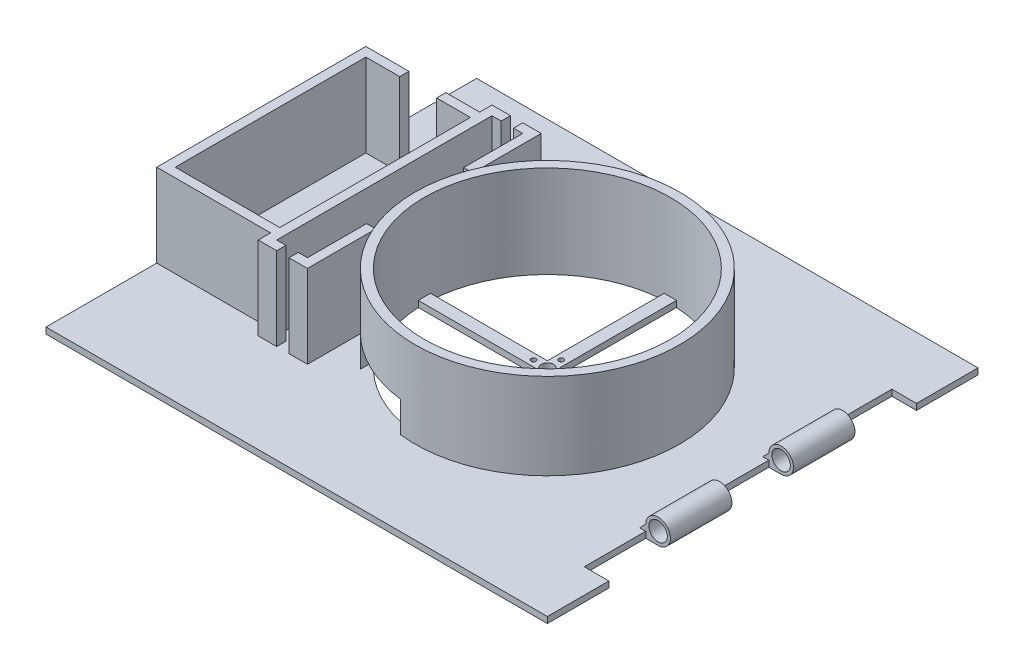
SolidWorks part; units mm, degrees
material "PLA"
ref_plane "Alzado" through (0, 0, 0) normal (0, 0, 1) x (1, 0, 0)
ref_plane "Planta" through (0, 0, 0) normal (0, 1, 0) x (1, 0, 0)
ref_plane "Vista lateral" through (0, 0, 0) normal (1, 0, 0) x (0, 0, -1)
sketch "Croquis1" plane through (0, 0, 0) normal (0, 1, 0) x (1, 0, 0)
  circle A0 centre (0, 0) radius 40
  circle A1 centre (0, 0) radius 43
  point P7 (0, 0)
  point P10 (0, 0)
  dimension "D1" = 80
  dimension "D2" = 3
extrude "Saliente-Extruir1" add sketch "Croquis1" along normal blind 30 contours A1 A0
sketch "Croquis3" plane through (0, 0, 0) normal (0, 1, 0) x (1, 0, 0)
  line L1 (0, -40) -> (0, 40) construction
  line L8 (-40, 0) -> (40, 0) construction
  line L13 (-2, 2) -> (-2, 39.95)
  line L18 (-2, -39.95) -> (-2, -2)
  line L20 (2, -39.95) -> (2, -2)
  line L22 (-1.9287, -39.9535) -> (1.9287, 39.9535) construction
  line L23 (-1.9287, 39.9535) -> (1.9287, -39.9535) construction
  line L24 (-39.95, -2) -> (-2, -2)
  line L27 (-39.95, 2) -> (-2, 2)
  line L29 (-39.9548, -1.9002) -> (39.9548, 1.9002) construction
  line L30 (-39.9548, 1.9002) -> (39.9548, -1.9002) construction
  line L31 (2, 2) -> (39.95, 2)
  line L32 (2, 2) -> (2, 39.95)
  line L33 (2, -2) -> (39.95, -2)
  circle A0 centre (0, 0) radius 40 construction
  circle A1 centre (0, 0) radius 40
  circle A2 centre (0, 0) radius 2
  circle A3 centre (4.5, 0) radius 0.81
  circle A9 centre (-4.5, 0) radius 0.81
  circle A11 centre (0, -4.5) radius 0.81
  circle A12 centre (0, 4.5) radius 0.81
  dimension "D3" = 1.62
  dimension "D4" = 4.5
  dimension "D5" = 1.62
  dimension "D1" = 4
  dimension "D2" = 4
  dimension "D6" = 4.5
extrude "Saliente-Extruir2" add sketch "Croquis3" along normal blind 2
sketch "Croquis4" plane through (0, 0, 0) normal (0, 1, 0) x (1, 0, 0)
  line L0 (0, 0) -> (43, 0) construction
  line L5 (-93, -70) -> (70, -70)
  line L6 (-93, -70) -> (-93, 70)
  line L7 (-93, 70) -> (70, 70)
  line L8 (70, -70) -> (70, 70)
  line L9 (-93, -70) -> (70, 70) construction
  line L10 (-93, 70) -> (70, -70) construction
  line L11 (0, 0) -> (-43, 0) construction
  circle A0 centre (0, 0) radius 43 construction
  circle A1 centre (0, 0) radius 43
  point P0 (0, 0)
  point P1 (-11.5, 0)
  dimension "D1" = 70
  dimension "D2" = 70
  dimension "D3" = 43
  dimension "D4" = 27
  dimension "D5" = 50
  dimension "D6" = 140
extrude "Saliente-Extruir3" add sketch "Croquis4" along normal blind 2
sketch "Croquis14" plane through (0, 2, 0) normal (0, 1, 0) x (1, 0, 0)
  line L1 (43, 0) -> (0, 0) construction
  line L2 (0, 0) -> (-43, 0) construction
  line L3 (-43, 0) -> (-93, 0) construction
  line L4 (70, -70) -> (70, 70)
  line L5 (70, 70) -> (-93, 70)
  line L6 (-93, 70) -> (-93, -70)
  line L7 (-93, -70) -> (70, -70)
  line L8 (70, -70) -> (70, 70)
  line L9 (70, 70) -> (-93, 70)
  line L10 (-93, 70) -> (-93, -70)
  line L11 (-93, -70) -> (70, -70)
  line L12 (0, 70) -> (0, 43) construction
  line L13 (0, 43) -> (0, -43) construction
  line L14 (0, -43) -> (0, -70) construction
  line L28 (43, 0) -> (40, 0)
  line L38 (-93, 70) -> (70, 70)
  line L39 (70, -70) -> (-93, -70)
  line L45 (-56, 38) -> (-40, 38)
  line L46 (-53, -34) -> (-93, -34)
  line L51 (-53, -34) -> (-53, 34)
  line L52 (-53, 34) -> (-93, 34)
  line L53 (-93, -34) -> (-93, 34)
  line L54 (-53, -34) -> (-93, 34) construction
  line L55 (-53, 34) -> (-93, -34) construction
  line L56 (-56, -31) -> (-90, -31)
  line L57 (-56, -31) -> (-56, 31)
  line L58 (-56, 31) -> (-90, 31)
  line L59 (-90, -31) -> (-90, 31)
  line L60 (-56, -31) -> (-90, 31) construction
  line L61 (-56, 31) -> (-90, -31) construction
  line L62 (-43, -35) -> (-53, -35)
  line L63 (-43, -35) -> (-43, 35)
  line L64 (-43, 35) -> (-53, 35)
  line L65 (-53, -35) -> (-53, 35)
  line L66 (-43, -35) -> (-53, 35) construction
  line L67 (-43, 35) -> (-53, -35) construction
  line L68 (-40, 0) -> (-40, 38)
  line L69 (-56, 38) -> (-56, 34)
  line L70 (-56, -31) -> (-56, -38)
  line L71 (-56, -38) -> (-40, -38)
  line L72 (-40, -38) -> (-40, 0)
  line L73 (-40, 15.7797) -> (-43, 15.7797)
  line L74 (-40, -15.7797) -> (-43, -15.7797)
  line L75 (-46, 38) -> (-46, 35)
  line L76 (-50, 38) -> (-50, 35)
  line L77 (-50, -35) -> (-50, -38)
  line L78 (-46, -35) -> (-46, -38)
  line L79 (-67, 34) -> (-67, 31)
  line L80 (-79, 34) -> (-79, 31)
  circle A0 centre (0, 0) radius 43 construction
  circle A1 centre (0, 0) radius 43 construction
  arc A2 (-43, 0) -> (-40, -15.7797) centre (0, 0) ccw
  arc A3 (-39.95, 2) -> (-39.95, -2) centre (0, 0) ccw construction
  arc A4 (-40, 15.7797) -> (-40, -15.7797) centre (0, 0) ccw
  arc A5 (0, -43) -> (40, 15.7797) centre (0, 0) ccw
  arc A6 (0, -43) -> (0, 43) centre (0, 0) ccw
  point P15 (-73, 0)
  point P24 (-73, 0)
  point P33 (-48, 0)
  dimension "D2" = 62
  dimension "D3" = 34
  dimension "D4" = 3
  dimension "D5" = 3
  dimension "D6" = 70
  dimension "D7" = 3
  dimension "D12" = 3
  dimension "D16" = 3
  dimension "D17" = 3
  dimension "D18" = 6
  dimension "D19" = 6
  dimension "D20" = 11
  dimension "D21" = 11
  dimension "D1" = 0
extrude "Saliente-Extruir17" add sketch "Croquis14" along normal blind 27 separate body contours L80 L52 L10 L46 L70 L56 L59 L58 | L52 L79 L58 L57 L70 L46 L51 | L77 L62 L65 L46 L70 L71 | L62 L78 L71 L72 L74 L63 | L45 L75 L64 L63 L73 L68 | L76 L45 L69 L52 L65 L64
sketch "Croquis15" plane through (0, 0, 70) normal (0, 0, 1) x (1, 0, 0)
  line L0 (43, 30) -> (-43, 30) construction
  line L1 (70, 2) -> (70, 0) construction
  line L3 (-5, 2) -> (-30, 2)
  line L4 (-5, 2) -> (-5, 12)
  line L5 (-5, 12) -> (-30, 12)
  line L6 (-30, 2) -> (-30, 12)
  dimension "D2" = 10
  dimension "D3" = 25
  dimension "D1" = 75
  dimension "D4" = 18
extrude "Cortar-Extruir1" cut sketch "Croquis15" against normal up to next
sketch "Croquis17" plane through (0, 2, 0) normal (0, 1, 0) x (1, 0, 0)
  line L0 (70, -70) -> (70, 70) construction
  line L1 (70, -50) -> (62, -50)
  line L2 (70, -50) -> (70, 50)
  line L3 (70, 50) -> (62, 50)
  line L4 (62, -50) -> (62, 50)
  line L5 (-93, -70) -> (70, -70) construction
  line L6 (70, 70) -> (-93, 70) construction
  dimension "D1" = 20
  dimension "D2" = 20
  dimension "D3" = 8
extrude "Cortar-Extruir2" cut sketch "Croquis17" against normal up to next (2 mm away)
sketch "Croquis18" plane through (0, 0, 50) normal (0, 0, -1) x (-1, 0, 0)
  line L2 (-62, 0) -> (-62, 2) construction
  line L4 (-62, 0) -> (-62, 2)
  line L6 (-62, 2) -> (-62, 7.7226) construction
  line L7 (-62, 0) -> (-71.0577, 0) construction
  line L8 (-62, 4) -> (-60, 2)
  line L9 (93, 2) -> (-70, 2) construction
  line L10 (-62, 0) -> (-66, 0)
  line L11 (-60, 2) -> (-62, 2)
  arc A0 (-62, 4) -> (-66, 0) centre (-66, 4) ccw
  circle A1 centre (-66, 4) radius 3
  dimension "D1" = 8
  dimension "D2" = 6
  dimension "D3" = 45
extrude "Saliente-Extruir19" add sketch "Croquis18" along normal blind 20 from offset 20
pattern_linear "MatrizL2" count 2 spacing 40 along (0, 0, -1) of "Saliente-Extruir19"
equation "\"D6@Croquis4\"=\"D2@Croquis4\"*2"
